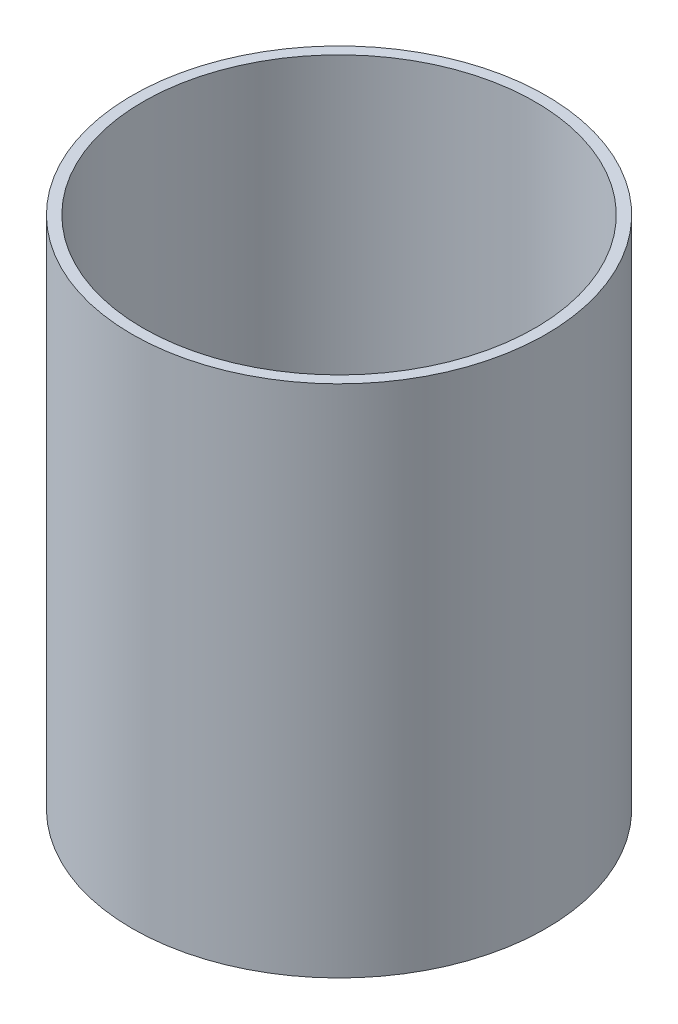
SolidWorks part; units mm, degrees
ref_plane "Front" through (0, 0, 0) normal (0, 0, 1) x (1, 0, 0)
ref_plane "Top" through (0, 0, 0) normal (0, 1, 0) x (1, 0, 0)
ref_plane "Right" through (0, 0, 0) normal (1, 0, 0) x (0, 0, -1)
sketch "Croquis1" plane through (0, 0, 0) normal (0, 1, 0) x (1, 0, 0)
  circle A0 centre (0, 0) radius 57.15
  circle A1 centre (0, 0) radius 60.325
  dimension "D1" = 114.3
  dimension "D2" = 3.175
extrude "Saliente-Extruir1" add sketch "Croquis1" along normal blind 150
